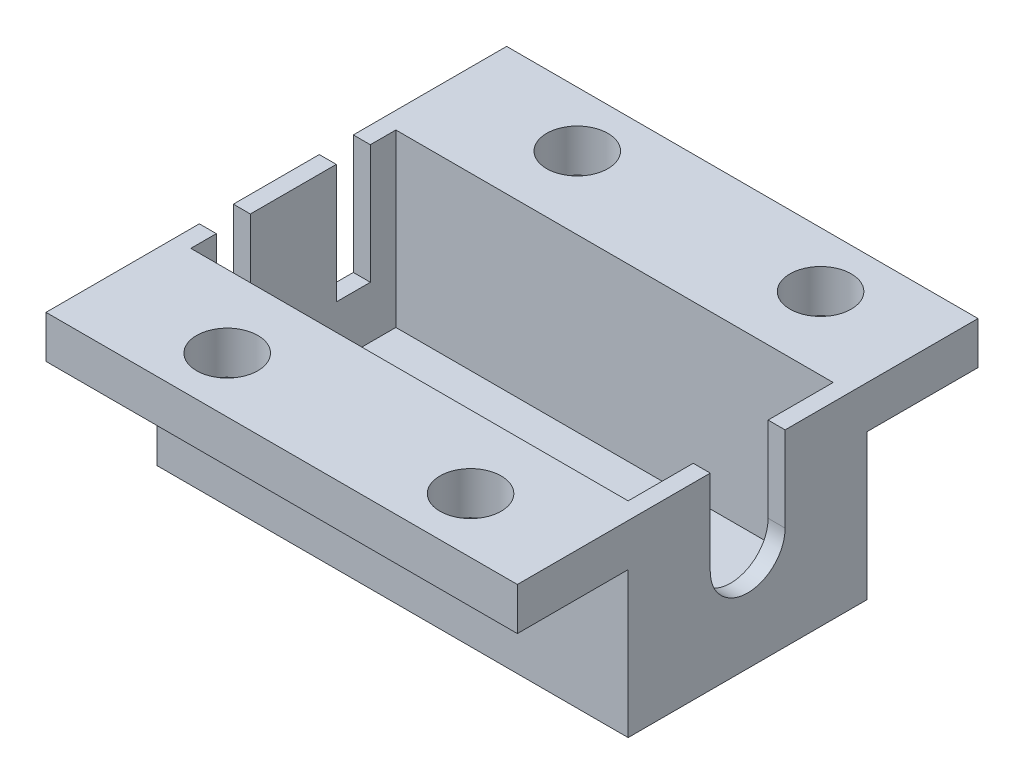
SolidWorks part; units mm, degrees
ref_plane "前视基准面" through (0, 0, 0) normal (0, 0, 1) x (1, 0, 0)
ref_plane "上视基准面" through (0, 0, 0) normal (0, 1, 0) x (1, 0, 0)
ref_plane "右视基准面" through (0, 0, 0) normal (1, 0, 0) x (0, 0, -1)
sketch "Sketch1" plane through (0, 0, 0) normal (0, 1, 0) x (1, 0, 0)
  line L1 (0, 0) -> (26.3, 0)
  line L2 (0, 0) -> (0, 14.05)
  line L3 (0, 14.05) -> (26.3, 14.05)
  line L4 (26.3, 0) -> (26.3, 14.05)
  dimension "D1" = 14.05
  dimension "D2" = 26.3
extrude "Boss-Extrude6" add sketch "Sketch1" along normal blind 1
sketch "Sketch5" plane through (0, 1, 0) normal (0, 1, 0) x (1, 0, 0)
  line L0 (0, 0) -> (26.3, 0) construction
  line L1 (0, 14.05) -> (1, 14.05)
  line L2 (0, 14.05) -> (0, 0)
  line L3 (0, 0) -> (1, 0)
  line L4 (1, 14.05) -> (1, 0)
  line L6 (26.3, 14.05) -> (25.3, 14.05)
  line L7 (26.3, 14.05) -> (26.3, 0)
  line L8 (26.3, 0) -> (25.3, 0)
  line L9 (25.3, 14.05) -> (25.3, 0)
  line L10 (25.3, 14.05) -> (1, 14.05)
  line L11 (25.3, 14.05) -> (25.3, 13.05)
  line L12 (25.3, 13.05) -> (1, 13.05)
  line L13 (1, 14.05) -> (1, 13.05)
  line L14 (1, 0) -> (25.3, 0)
  line L15 (1, 0) -> (1, 1)
  line L16 (1, 1) -> (25.3, 1)
  line L17 (25.3, 0) -> (25.3, 1)
  line M1 (0, 14.05) -> (0, 0)
  line M2 (0, 0) -> (26.3, 0)
  line M3 (26.3, 0) -> (26.3, 14.05)
  line M4 (26.3, 14.05) -> (0, 14.05)
  dimension "D1" = 1
  dimension "D2" = 1
  dimension "D3" = 1
  dimension "D4" = 1
extrude "Boss-Extrude8" add sketch "Sketch5" along normal blind 10.05 contours L12 L9 L4 M4 | L9 M4 M2 M3 | L16 L4 L9 M2 | L4 M4 M1 M2
sketch "Sketch6" plane through (0, 11.05, 0) normal (0, 1, 0) x (1, 0, 0)
  line L0 (0, 0) -> (26.3, 0) construction
  line L1 (0, -6.51) -> (26.3, -6.51)
  line L2 (0, -6.51) -> (0, 20.56)
  line L3 (0, 20.56) -> (26.3, 20.56)
  line L4 (26.3, -6.51) -> (26.3, 20.56)
  line L5 (26.3, 14.05) -> (0, 14.05) construction
  line L6 (25.3, 13.05) -> (25.3, 1) construction
  line L7 (1, 1) -> (25.3, 1)
  line L8 (1, 1) -> (1, 13.05)
  line L9 (1, 13.05) -> (25.3, 13.05)
  line L10 (25.3, 1) -> (25.3, 13.05)
  dimension "D1" = 6.51
  dimension "D2" = 6.51
extrude "Boss-Extrude9" add sketch "Sketch6" against normal blind 2.5
sketch "Sketch7" plane through (0, 11.05, 0) normal (0, 1, 0) x (1, 0, 0)
  line L0 (-5.2433, -3.26) -> (29.4567, -3.26) construction
  line L1 (-5.2433, 17.31) -> (29.4567, 17.31) construction
  line L2 (0, -6.51) -> (26.3, -6.51) construction
  line L3 (26.3, 20.56) -> (0, 20.56) construction
  line L4 (0, 20.56) -> (0, -6.51) construction
  line L5 (26.3, -6.51) -> (26.3, 20.56) construction
  circle A0 centre (6, -3.26) radius 1.8
  circle A1 centre (20.3, -3.26) radius 1.8
  circle A2 centre (6, 17.31) radius 1.8
  circle A3 centre (20.3, 17.31) radius 1.8
  dimension "D3" = 3.6
  dimension "D4" = 3.6
  dimension "D7" = 3.6
  dimension "D8" = 3.6
  dimension "D1" = 3.25
  dimension "D2" = 3.25
  dimension "D5" = 6
  dimension "D6" = 6
  dimension "D9" = 6
  dimension "D10" = 6
extrude "Cut-Extrude1" cut sketch "Sketch7" against normal blind 2.5
sketch "Sketch8" plane through (26.3, 0, 0) normal (1, 0, 0) x (0, 0, -1)
  line L0 (7.025, 11.05) -> (7.025, -3.7123) construction
  line L1 (-6.51, 11.05) -> (20.56, 11.05) construction
  line L3 (9.225, 11.05) -> (4.825, 11.05)
  line L4 (9.225, 11.05) -> (9.225, 6.05)
  line L5 (9.225, 6.05) -> (4.825, 6.05)
  line L6 (4.825, 11.05) -> (4.825, 6.05)
  dimension "D1" = 2.2
  dimension "D2" = 2.2
  dimension "D3" = 5
extrude "Cut-Extrude2" cut sketch "Sketch8" against normal blind 2.5
sketch "Sketch9" plane through (26.3, 0, 0) normal (1, 0, 0) x (0, 0, -1)
  line L0 (4.825, 6.05) -> (9.225, 6.05) construction
  line L1 (9.225, 6.05) -> (4.825, 6.05)
  arc A0 (4.825, 6.05) -> (9.225, 6.05) centre (7.025, 6.05) ccw
extrude "Cut-Extrude3" cut sketch "Sketch9" against normal blind 2.5
sketch "Sketch10" plane through (0, 0, 0) normal (0, -1, 0) x (1, 0, 0)
  line L0 (0, -14.05) -> (0, 0) construction
  line L1 (14.5, -11.025) -> (2.5, -11.025)
  line L2 (14.5, -11.025) -> (14.5, -3.025)
  line L3 (14.5, -3.025) -> (2.5, -3.025)
  line L4 (2.5, -11.025) -> (2.5, -3.025)
  point P4 (0, -7.025)
  dimension "D1" = 12
  dimension "D2" = 8
  dimension "D3" = 4
  dimension "D4" = 2.5
extrude "Cut-Extrude5" cut sketch "Sketch10" against normal blind 2.5
sketch "Sketch11" plane through (0, 0, 0) normal (-1, 0, 0) x (0, 0, 1)
  line L0 (-20.56, 11.05) -> (6.51, 11.05) construction
  line L1 (-2.5, 11.05) -> (-4.5, 11.05)
  line L2 (-2.5, 11.05) -> (-2.5, 4.05)
  line L3 (-2.5, 4.05) -> (-4.5, 4.05)
  line L4 (-4.5, 11.05) -> (-4.5, 4.05)
  line L5 (0, 8.55) -> (0, 0) construction
  line L6 (-9.55, 11.05) -> (-11.55, 11.05)
  line L7 (-9.55, 11.05) -> (-9.55, 4.05)
  line L8 (-9.55, 4.05) -> (-11.55, 4.05)
  line L9 (-11.55, 11.05) -> (-11.55, 4.05)
  line L10 (-14.05, 8.55) -> (-14.05, 0) construction
  dimension "D1" = 2.5
  dimension "D2" = 2
  dimension "D3" = 2
  dimension "D4" = 2.5
  dimension "D5" = 7
  dimension "D6" = 7
extrude "Cut-Extrude7" cut sketch "Sketch11" against normal blind 2.5
sketch "Sketch12" plane through (0, 0, 0) normal (-1, 0, 0) x (0, 0, 1)
  line L0 (-4.5, 11.05) -> (-4.5, 4.05) construction
  line L1 (-2.5, 11.05) -> (-4.5, 11.05)
  line L2 (-2.5, 11.05) -> (-2.5, 8.05)
  line L3 (-2.5, 8.05) -> (-4.5, 8.05)
  line L4 (-4.5, 11.05) -> (-4.5, 8.05)
  line L5 (-11.55, 11.05) -> (-11.55, 4.05) construction
  line L6 (-9.55, 11.05) -> (-11.55, 11.05)
  line L7 (-9.55, 11.05) -> (-9.55, 8.05)
  line L8 (-9.55, 8.05) -> (-11.55, 8.05)
  line L9 (-11.55, 11.05) -> (-11.55, 8.05)
  dimension "D1" = 3
  dimension "D2" = 3
extrude "Boss-Extrude11" add sketch "Sketch12" against normal blind 1
sketch "Sketch13" plane through (0, 0, 0) normal (0, -1, 0) x (1, 0, 0)
  line L0 (2.5, -11.025) -> (14.5, -11.025) construction
  line L1 (2.5, -3.025) -> (4.5, -3.025)
  line L2 (2.5, -3.025) -> (2.5, -11.025)
  line L3 (2.5, -11.025) -> (4.5, -11.025)
  line L4 (4.5, -3.025) -> (4.5, -11.025)
  dimension "D1" = 2
extrude "Boss-Extrude14" add sketch "Sketch13" against normal blind 1
sketch "Sketch14" plane through (0, 0, 0) normal (-1, 0, 0) x (0, 0, 1)
  line L0 (-20.56, 8.55) -> (-14.05, 8.55)
  line L1 (-14.05, 8.55) -> (-14.05, 0)
  line L2 (-14.05, 0) -> (0, 0)
  line L3 (0, 0) -> (0, 8.55)
  line L4 (0, 8.55) -> (6.51, 8.55)
  line L5 (6.51, 8.55) -> (6.51, 11.05)
  line L6 (6.51, 11.05) -> (-20.56, 11.05)
  line L7 (-20.56, 11.05) -> (-20.56, 8.55)
  line L9 (-11.55, 4.05) -> (-9.55, 4.05)
  line L10 (-11.55, 4.05) -> (-11.55, 8.05)
  line L11 (-11.55, 8.05) -> (-9.55, 8.05)
  line L12 (-9.55, 4.05) -> (-9.55, 8.05)
  line L13 (-4.5, 4.05) -> (-2.5, 4.05)
  line L14 (-4.5, 4.05) -> (-4.5, 8.05)
  line L15 (-4.5, 8.05) -> (-2.5, 8.05)
  line L16 (-2.5, 4.05) -> (-2.5, 8.05)
extrude "Boss-Extrude15" add sketch "Sketch14" along normal blind 1.4
sketch "Sketch15" plane through (1, 0, 0) normal (1, 0, 0) x (0, 0, -1)
  line L1 (13.05, 11.05) -> (1, 11.05)
  line L2 (13.05, 11.05) -> (13.05, 1)
  line L3 (13.05, 1) -> (1, 1)
  line L4 (1, 11.05) -> (1, 1)
extrude "Cut-Extrude8" cut sketch "Sketch15" against normal blind 1.4
sketch "Sketch16" plane through (-1.4, 0, 0) normal (-1, 0, 0) x (0, 0, 1)
  line L0 (6.51, 11.05) -> (-20.56, 11.05) construction
  line L1 (-11.55, 8.05) -> (-9.55, 8.05)
  line L2 (-11.55, 8.05) -> (-11.55, 11.05)
  line L3 (-11.55, 11.05) -> (-9.55, 11.05)
  line L4 (-9.55, 8.05) -> (-9.55, 11.05)
  line L6 (-4.5, 8.05) -> (-2.5, 8.05)
  line L7 (-4.5, 8.05) -> (-4.5, 11.05)
  line L8 (-4.5, 11.05) -> (-2.5, 11.05)
  line L9 (-2.5, 8.05) -> (-2.5, 11.05)
extrude "Cut-Extrude9" cut sketch "Sketch16" against normal blind 1.4
